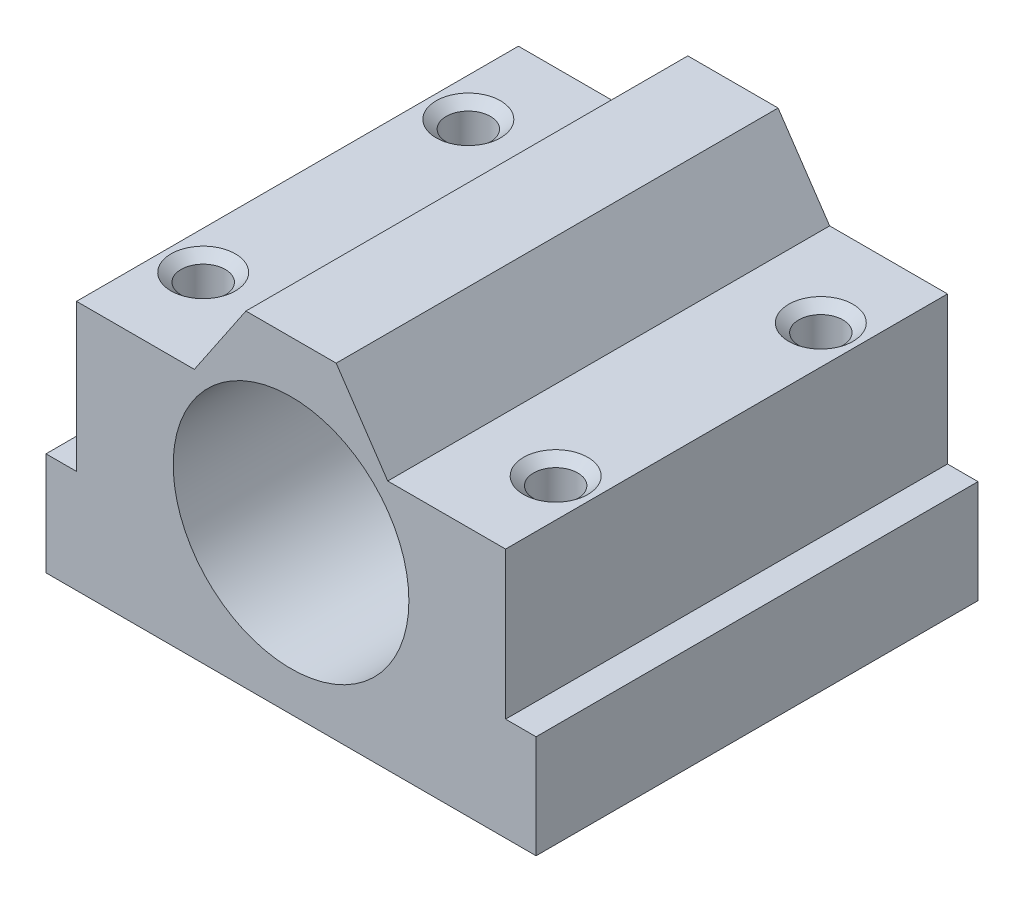
SolidWorks part; units mm, degrees
ref_plane "Front Plane" through (0, 0, 0) normal (0, 0, 1) x (1, 0, 0)
ref_plane "Top Plane" through (0, 0, 0) normal (0, 1, 0) x (1, 0, 0)
ref_plane "Right Plane" through (0, 0, 0) normal (1, 0, 0) x (0, 0, -1)
sketch "Sketch1" plane through (0, 0, 0) normal (0, 0, 1) x (1, 0, 0)
  line L5 (33.27, 7) -> (31.1994, 7)
  line L7 (31.1994, 7) -> (31.1994, 17)
  line L8 (33.27, 0) -> (33.27, 7)
  line L9 (31.1994, 17) -> (23.1994, 17)
  line L11 (0, 0) -> (33.27, 0)
  line L13 (2.0706, 17) -> (10.0706, 17)
  line L14 (2.0706, 7) -> (2.0706, 17)
  line L15 (0, 7) -> (2.0706, 7)
  line L16 (0, 0) -> (0, 7)
  line L17 (13.5706, 22.18) -> (19.6994, 22.18)
  line L18 (23.1994, 17) -> (19.6994, 22.18)
  line L20 (10.0706, 17) -> (13.5706, 22.18)
  circle A0 centre (16.635, 10.68) radius 8
extrude "Boss-Extrude1" add sketch "Sketch1" along normal blind 30
sketch "Sketch2" plane through (0, 17, 0) normal (0, 1, 0) x (1, 0, 0)
  circle A0 centre (28.5994, -6) radius 1.5
  circle A1 centre (28.5994, -24) radius 1.5
  circle A2 centre (4.6706, -24) radius 1.5
  circle A3 centre (4.6706, -6) radius 1.5
extrude "Cut-Extrude2" cut sketch "Sketch2" against normal blind 30
hole_wizard "CSK for #2 Flat Head Machine Screw (100)1" positions "Sketch8" profile "Sketch9" countersink size "#2" standard "ANSI Inch" end condition through all
sketch "Sketch8" plane through (0, 17, 0) normal (0, 1, 0) x (1, 0, 0)
  point P0 (4.6706, -6)
sketch "Sketch9" plane through (4.6706, 17, 6) normal (1, 0, 0) x (0, 0, 1)
  line L0 (0, 0) -> (0, 17)
  line L1 (0, 17) -> (1.3525, 17)
  line L2 (1.3525, 17) -> (1.3525, 0.698)
  line L3 (1.3525, 0.698) -> (2.1844, 0)
  line L5 (2.1844, 0) -> (0, 0)
  line L6 (-1.3525, 0.698) -> (-2.1844, 0) construction
  line L11 (0, -6.35) -> (0, 107.95) construction
  dimension "Thru Hole Dia." = 2.7051
  dimension "Thru Hole Depth" = 17
  dimension "Near C'Sink Dia." = 4.3688
  dimension "Near C'Sink Angle" = 100
hole_wizard "CSK for #2 Flat Head Machine Screw (100)2" positions "Sketch10" profile "Sketch11" countersink size "#2" standard "ANSI Inch" end condition through all
sketch "Sketch10" plane through (0, 17, 0) normal (0, 1, 0) x (1, 0, 0)
  point P0 (4.6706, -24)
sketch "Sketch11" plane through (4.6706, 17, 24) normal (1, 0, 0) x (0, 0, 1)
  line L0 (0, 0) -> (0, 17)
  line L1 (0, 17) -> (1.3525, 17)
  line L2 (1.3525, 17) -> (1.3525, 0.698)
  line L3 (1.3525, 0.698) -> (2.1844, 0)
  line L5 (2.1844, 0) -> (0, 0)
  line L6 (-1.3525, 0.698) -> (-2.1844, 0) construction
  line L11 (0, -6.35) -> (0, 107.95) construction
  dimension "Thru Hole Dia." = 2.7051
  dimension "Thru Hole Depth" = 17
  dimension "Near C'Sink Dia." = 4.3688
  dimension "Near C'Sink Angle" = 100
hole_wizard "CSK for #2 Flat Head Machine Screw (100)3" positions "Sketch12" profile "Sketch13" countersink size "#2" standard "ANSI Inch" end condition through all
sketch "Sketch12" plane through (0, 17, 0) normal (0, 1, 0) x (1, 0, 0)
  point P0 (28.5994, -6)
sketch "Sketch13" plane through (28.5994, 17, 6) normal (1, 0, 0) x (0, 0, 1)
  line L0 (0, 0) -> (0, 17)
  line L1 (0, 17) -> (1.3525, 17)
  line L2 (1.3525, 17) -> (1.3525, 0.698)
  line L3 (1.3525, 0.698) -> (2.1844, 0)
  line L5 (2.1844, 0) -> (0, 0)
  line L6 (-1.3525, 0.698) -> (-2.1844, 0) construction
  line L11 (0, -6.35) -> (0, 107.95) construction
  dimension "Thru Hole Dia." = 2.7051
  dimension "Thru Hole Depth" = 17
  dimension "Near C'Sink Dia." = 4.3688
  dimension "Near C'Sink Angle" = 100
hole_wizard "CSK for #2 Flat Head Machine Screw (100)4" positions "Sketch14" profile "Sketch15" countersink size "#2" standard "ANSI Inch" end condition through all
sketch "Sketch14" plane through (0, 17, 0) normal (0, 1, 0) x (1, 0, 0)
  point P0 (28.5994, -24)
sketch "Sketch15" plane through (28.5994, 17, 24) normal (1, 0, 0) x (0, 0, 1)
  line L0 (0, 0) -> (0, 17)
  line L1 (0, 17) -> (1.3525, 17)
  line L2 (1.3525, 17) -> (1.3525, 0.698)
  line L3 (1.3525, 0.698) -> (2.1844, 0)
  line L5 (2.1844, 0) -> (0, 0)
  line L6 (-1.3525, 0.698) -> (-2.1844, 0) construction
  line L11 (0, -6.35) -> (0, 107.95) construction
  dimension "Thru Hole Dia." = 2.7051
  dimension "Thru Hole Depth" = 17
  dimension "Near C'Sink Dia." = 4.3688
  dimension "Near C'Sink Angle" = 100
sketch "Sketch16" plane through (0, 0, 0) normal (0, -1, 0) x (-1, 0, 0)
  line L0 (-4.6706, -24) -> (-28.5994, -24)
  line L1 (-28.5994, -24) -> (-33.27, -24)
  line L2 (-33.27, -30) -> (-33.27, 0) construction
  line L3 (-4.6706, -24) -> (0, -24)
  line L4 (0, -30) -> (0, 0) construction
  line L5 (-4.6706, -24) -> (-4.6706, -30)
  line L6 (0, -30) -> (-33.27, -30) construction
  line L7 (-16.635, -30) -> (-16.635, 0)
  line L8 (0, 0) -> (-33.27, 0) construction
  dimension "D1" = 23.9287
  dimension "D2" = 4.6706
  dimension "D3" = 6
  dimension "D4" = 30
